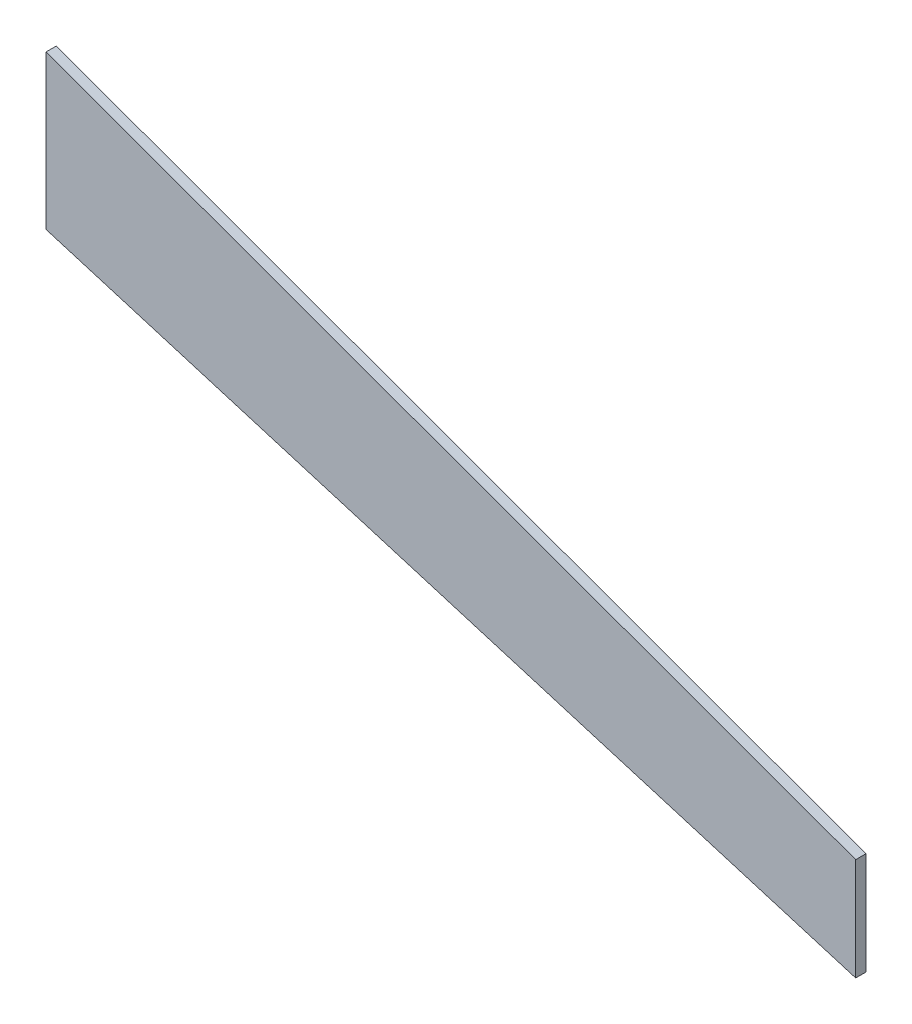
SolidWorks part; units mm, degrees
ref_plane "Ebene vorne" through (0, 0, 0) normal (0, 0, 1) x (1, 0, 0)
ref_plane "Ebene oben" through (0, 0, 0) normal (0, 1, 0) x (1, 0, 0)
ref_plane "Ebene rechts" through (0, 0, 0) normal (1, 0, 0) x (0, 0, -1)
sketch "Sketch1" plane through (0, 0, 0) normal (0, 0, 1) x (1, 0, 0)
  line L0 (0, 60) -> (0, 0)
  line L1 (316, -55.0146) -> (316, -95.0146)
  line L2 (316, -95.0146) -> (0, 0)
  line L3 (316, -55.0146) -> (0, 60)
  line L4 (0, 60) -> (142.7808, 60) construction
  dimension "D1" = 20
  dimension "D2" = 40
  dimension "D3" = 60
  dimension "D4" = 316
extrude "Boss-Extrude1" add sketch "Sketch1" along normal blind 4
